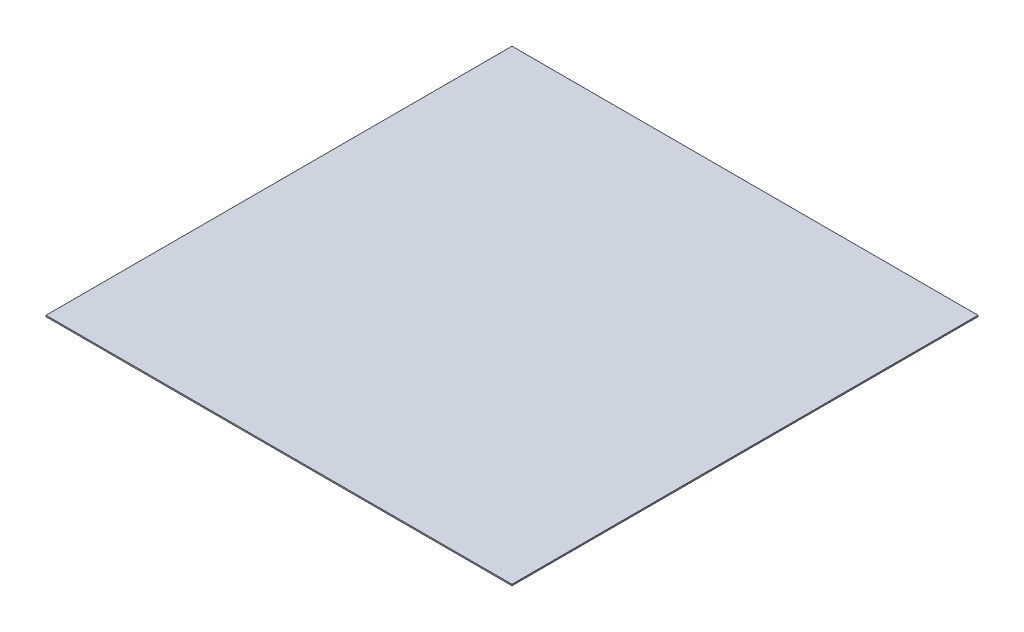
SolidWorks part; units mm, degrees
ref_plane "Front Plane" through (0, 0, 0) normal (0, 0, 1) x (1, 0, 0)
ref_plane "Top Plane" through (0, 0, 0) normal (0, 1, 0) x (1, 0, 0)
ref_plane "Right Plane" through (0, 0, 0) normal (1, 0, 0) x (0, 0, -1)
sketch "Sketch1" plane through (0, 0, 0) normal (0, 1, 0) x (1, 0, 0)
  line L0 (-1.397, 0) -> (1.397, 0) construction
  line L1 (-457.2, -457.2) -> (457.2, -457.2)
  line L2 (-457.2, -457.2) -> (-457.2, 457.2)
  line L3 (-457.2, 457.2) -> (457.2, 457.2)
  line L4 (457.2, -457.2) -> (457.2, 457.2)
  line L5 (-457.2, -457.2) -> (457.2, 457.2) construction
  line L6 (-457.2, 457.2) -> (457.2, -457.2) construction
  point P0 (0, 0)
  point P7 (0, 0)
  dimension "D1" = 914.4
  dimension "D2" = 914.4
extrude "Boss-Extrude1" add sketch "Sketch1" along normal mid plane 2.54 contours L3 L4 L1 L2
